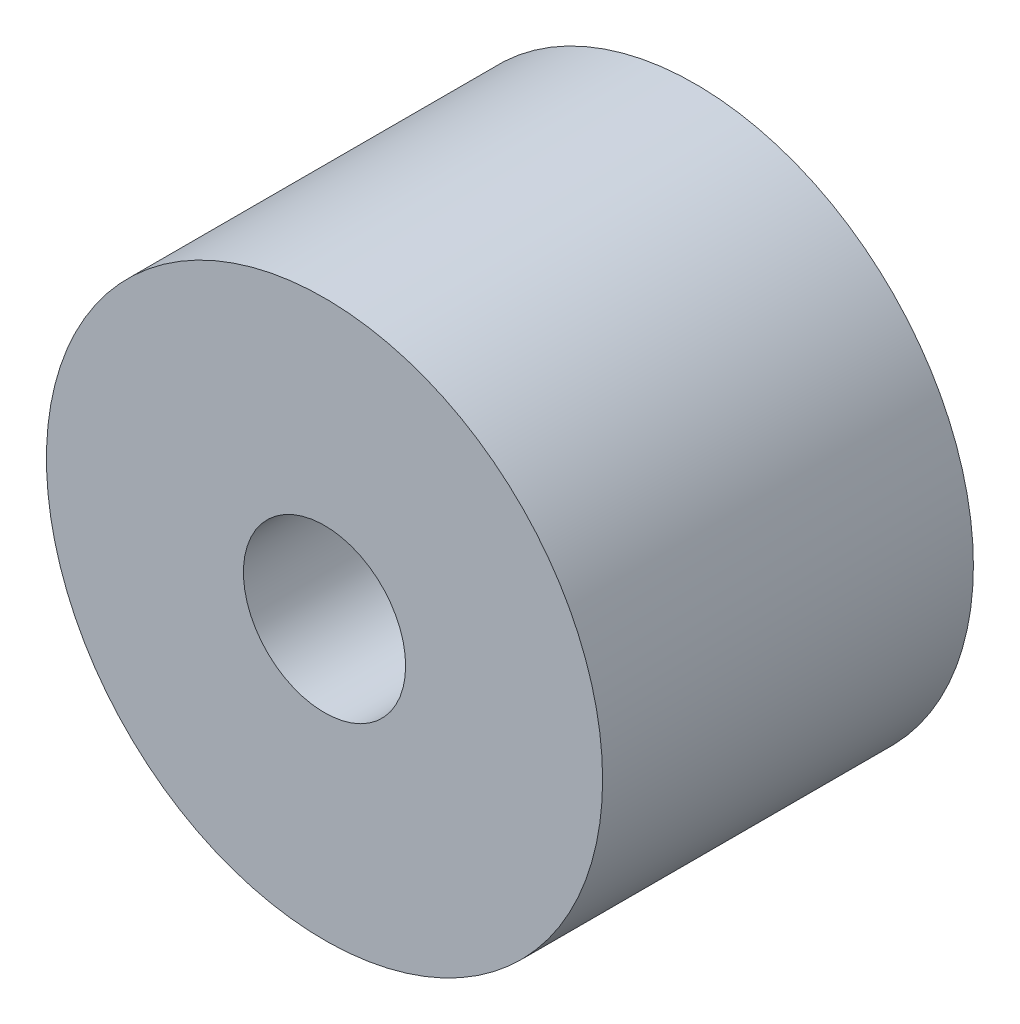
SolidWorks part; units mm, degrees
material "PET"
ref_plane "Alzado" through (0, 0, 0) normal (0, 0, 1) x (1, 0, 0)
ref_plane "Planta" through (0, 0, 0) normal (0, 1, 0) x (1, 0, 0)
ref_plane "Vista lateral" through (0, 0, 0) normal (1, 0, 0) x (0, 0, -1)
sketch "Croquis1" plane through (0, 0, 0) normal (0, 0, 1) x (1, 0, 0)
  circle A0 centre (0, 0) radius 19.05
  circle A1 centre (0, 0) radius 5.5562
  dimension "D1" = 38.1
  dimension "D2" = 11.1125
extrude "Saliente-Extruir1" add sketch "Croquis1" along normal mid plane 25.4
